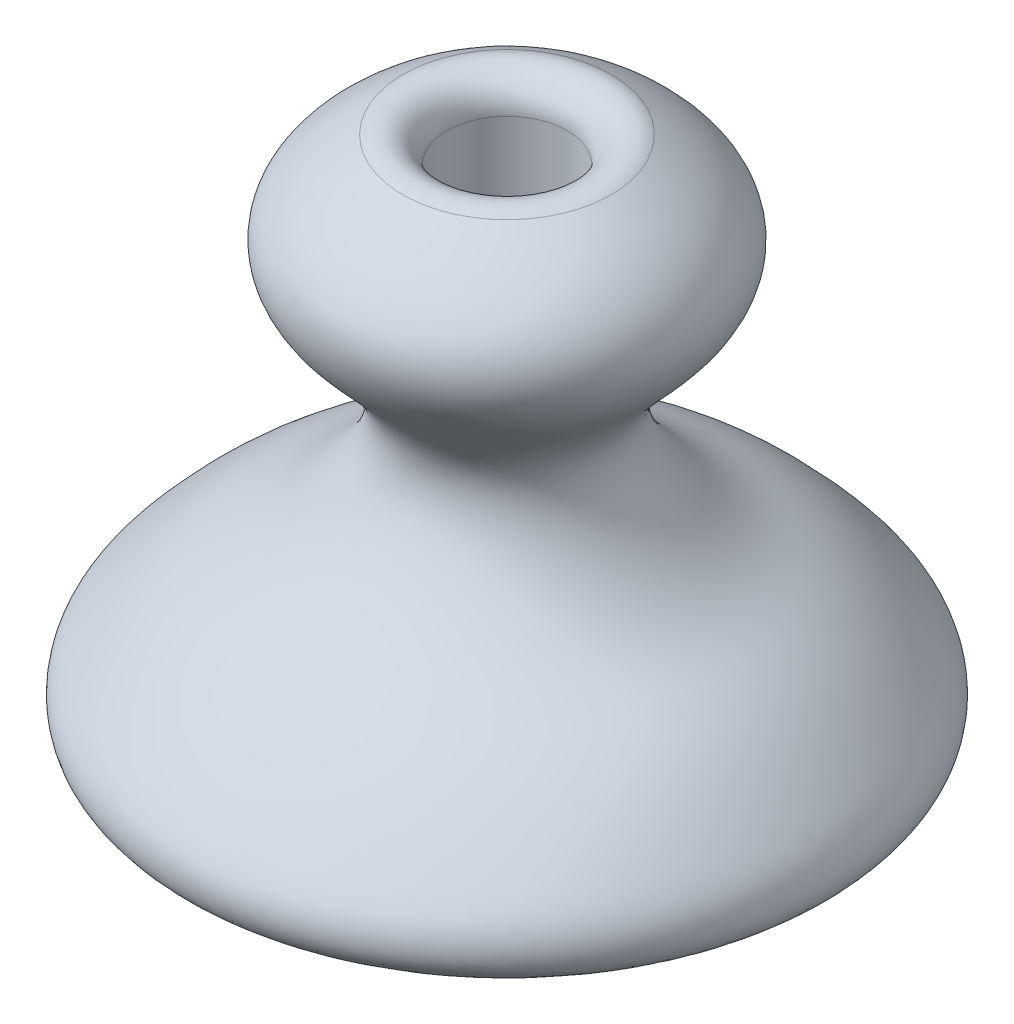
SolidWorks part; units mm, degrees
ref_plane "前视基准面" through (0, 0, 0) normal (0, 0, 1) x (1, 0, 0)
ref_plane "上视基准面" through (0, 0, 0) normal (0, 1, 0) x (1, 0, 0)
ref_plane "右视基准面" through (0, 0, 0) normal (1, 0, 0) x (0, 0, -1)
other "Configuration Table"
sketch "草图2" plane through (0, 0, 0) normal (1, 0, 0) x (0, 0, -1)
  line L0 (0, 0) -> (0, 36.9439)
  line L1 (0, 0) -> (20.0808, 0)
  spline S0 degree 3 poles (20.0808, 0) (21.6199, 0.3962) (22.0482, 2.703) (16.3184, 9.5545) (12.0125, 9.6681) (4.1365, 18.9086) (15.7867, 28.1082) (10.5058, 33.6811) (0, 36.9439) knots 0 0 0 0 0.042122 0.074303 0.321814 0.524436 0.65007 1 1 1 1
  point P5 (0, 0)
  point P7 (21.3356, 2.3904)
  point P9 (0, 36.2059)
  point P11 (11.0818, 30.1941)
  point P13 (6.862, 19.0955)
  point P15 (10.4697, 8.592)
  point P16 (10.9651, 11.8308)
  point P17 (0, 37.2552)
revolve "旋转1" add sketch "草图2" angle 360 about L0
ref_plane "基准面1" through (0, 5, 0) normal (0, -1, 0) x (-1, 0, 0)
sketch "草图3" plane through (0, 5, 0) normal (0, -1, 0) x (-1, 0, 0)
  circle A0 centre (0, 0) radius 4
  dimension "D1" = 8
extrude "切除-拉伸1" cut sketch "草图3" against normal through all
sketch "草图4" plane through (0, 5, 0) normal (0, 1, 0) x (1, 0, 0)
  circle A0 centre (0, 0) radius 1.65
  dimension "D1" = 3.3
extrude "切除-拉伸2" cut sketch "草图4" against normal through all
fillet "圆角1" radius 2 1 edges at (0, 35.5338, -4)
